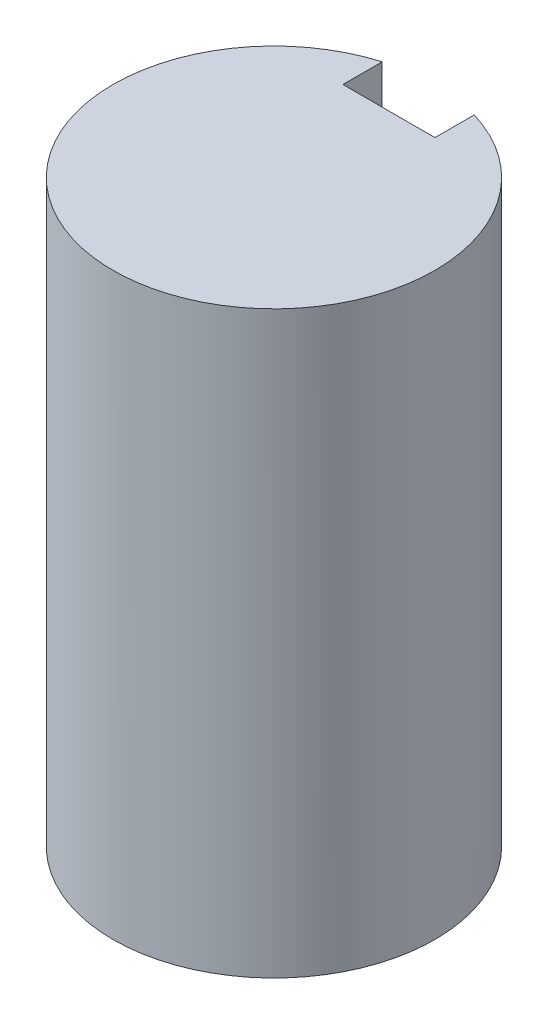
SolidWorks part; units mm, degrees
ref_plane "Front Plane" through (0, 0, 0) normal (0, 0, 1) x (1, 0, 0)
ref_plane "Top Plane" through (0, 0, 0) normal (0, 1, 0) x (1, 0, 0)
ref_plane "Right Plane" through (0, 0, 0) normal (1, 0, 0) x (0, 0, -1)
sketch "Sketch1" plane through (0, 0, 0) normal (0, 1, 0) x (1, 0, 0)
  circle A0 centre (0, 0) radius 17.5
  dimension "D1" = 35
extrude "Boss-Extrude1" add sketch "Sketch1" along normal blind 63
sketch "Sketch2" plane through (0, 63, 0) normal (0, 1, 0) x (1, 0, 0)
  line L0 (0, 17.5) -> (0, 12.5) construction
  line L1 (-5, 12.5) -> (5, 12.5)
  line L2 (5, 12.5) -> (5, 16.7705)
  line L3 (-5, 12.5) -> (-5, 16.7705)
  arc A0 (5, 16.7705) -> (-5, 16.7705) centre (0, 0) ccw
  dimension "D2" = 35
  dimension "D1" = 12.5
  dimension "D3" = 5
extrude "Cut-Extrude1" cut sketch "Sketch2" against normal blind 35
